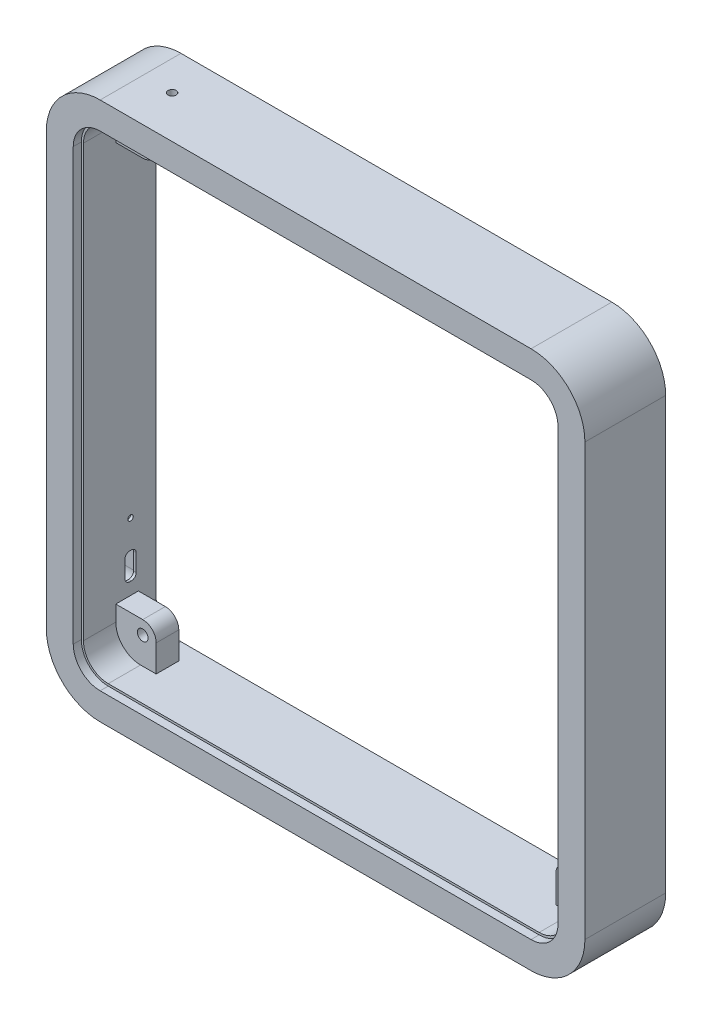
SolidWorks part; units mm, degrees
ref_plane "Piano frontale" through (0, 0, 0) normal (0, 0, 1) x (1, 0, 0)
ref_plane "Piano superiore" through (0, 0, 0) normal (0, 1, 0) x (1, 0, 0)
ref_plane "Piano destro" through (0, 0, 0) normal (1, 0, 0) x (0, 0, -1)
sketch "Sketch2" plane through (0, 0, 0) normal (0, 0, 1) x (1, 0, 0)
  line L5 (-100, -100) -> (100, -100)
  line L6 (-100, -100) -> (-100, 100)
  line L7 (-100, 100) -> (100, 100)
  line L8 (100, -100) -> (100, 100)
  line L9 (-100, -100) -> (100, 100) construction
  line L10 (-100, 100) -> (100, -100) construction
  point P0 (0, 0)
  dimension "D1" = 200
extrude "Boss-Extrude1" add sketch "Sketch2" along normal blind 30
fillet "Fillet1" radius 20 4 edges at (-100, -100, 15) (100, -100, 15) (100, 100, 15) (-100, 100, 15)
sketch "Sketch3" plane through (0, 0, 30) normal (0, 0, 1) x (1, 0, 0)
  line L8 (-90, 80) -> (-90, -80)
  line L9 (-80, -90) -> (80, -90)
  line L10 (90, -80) -> (90, 80)
  line L11 (80, 90) -> (-80, 90)
  line L12 (-90, 80) -> (-90, -80)
  line L13 (-80, -90) -> (80, -90)
  line L14 (90, -80) -> (90, 80)
  line L15 (80, 90) -> (-80, 90)
  arc A8 (-90, -80) -> (-80, -90) centre (-80, -80) ccw
  arc A9 (80, -90) -> (90, -80) centre (80, -80) ccw
  arc A10 (90, 80) -> (80, 90) centre (80, 80) ccw
  arc A11 (-80, 90) -> (-90, 80) centre (-80, 80) ccw
  arc A12 (-90, -80) -> (-80, -90) centre (-80, -80) ccw
  arc A13 (80, -90) -> (90, -80) centre (80, -80) ccw
  arc A14 (90, 80) -> (80, 90) centre (80, 80) ccw
  arc A15 (-80, 90) -> (-90, 80) centre (-80, 80) ccw
  dimension "D1" = 10
extrude "Cut-Extrude1" cut sketch "Sketch3" against normal blind 3
sketch "Sketch4" plane through (0, 0, 27) normal (0, 0, 1) x (1, 0, 0)
  line L16 (-89.2, 80) -> (-89.2, -80)
  line L17 (-80, -89.2) -> (80, -89.2)
  line L18 (89.2, -80) -> (89.2, 80)
  line L19 (80, 89.2) -> (-80, 89.2)
  line L20 (-89.2, 80) -> (-89.2, -80)
  line L21 (-80, -89.2) -> (80, -89.2)
  line L22 (89.2, -80) -> (89.2, 80)
  line L23 (80, 89.2) -> (-80, 89.2)
  arc A16 (-80, 89.2) -> (-89.2, 80) centre (-80, 80) ccw
  arc A17 (-89.2, -80) -> (-80, -89.2) centre (-80, -80) ccw
  arc A18 (80, -89.2) -> (89.2, -80) centre (80, -80) ccw
  arc A19 (89.2, 80) -> (80, 89.2) centre (80, 80) ccw
  arc A20 (-80, 89.2) -> (-89.2, 80) centre (-80, 80) ccw
  arc A21 (-89.2, -80) -> (-80, -89.2) centre (-80, -80) ccw
  arc A22 (80, -89.2) -> (89.2, -80) centre (80, -80) ccw
  arc A23 (89.2, 80) -> (80, 89.2) centre (80, 80) ccw
  dimension "D1" = 0.8
extrude "Cut-Extrude2" cut sketch "Sketch4" against normal through all
sketch "Sketch6" plane through (0, 0, 0) normal (0, 0, -1) x (-1, 0, 0)
  line L1 (-89.2, -74.2) -> (-74.2, -74.2)
  line L2 (-89.2, -74.2) -> (-89.2, -89.2)
  line L3 (-89.2, -89.2) -> (-74.2, -89.2)
  line L4 (-74.2, -74.2) -> (-74.2, -89.2)
  line L5 (-89.2, -80) -> (-89.2, 80) construction
  line L6 (80, -89.2) -> (-80, -89.2) construction
  line L18 (-74.2, 89.2) -> (-74.2, 74.2)
  line L19 (-89.2, 89.2) -> (89.2, 89.2) construction
  line L20 (-89.2, 89.2) -> (-89.2, -89.2) construction
  line L21 (-89.2, -89.2) -> (89.2, -89.2) construction
  line L22 (89.2, 89.2) -> (89.2, -89.2) construction
  line L23 (-89.2, 89.2) -> (89.2, -89.2) construction
  line L24 (-89.2, -89.2) -> (89.2, 89.2) construction
  line L25 (-74.2, 74.2) -> (-89.2, 74.2)
  line L26 (-89.2, 89.2) -> (-89.2, 74.2)
  line L27 (-74.2, 89.2) -> (-89.2, 89.2)
  line L28 (89.2, 74.2) -> (74.2, 74.2)
  line L29 (74.2, 74.2) -> (74.2, 89.2)
  line L30 (89.2, 89.2) -> (74.2, 89.2)
  line L31 (89.2, 74.2) -> (89.2, 89.2)
  line L32 (74.2, -89.2) -> (74.2, -74.2)
  line L33 (74.2, -74.2) -> (89.2, -74.2)
  line L34 (89.2, -89.2) -> (89.2, -74.2)
  line L35 (74.2, -89.2) -> (89.2, -89.2)
  point P14 (0, 0)
  point P19 (0, 0)
  point P24 (0, 0)
  point P29 (0, 0)
  dimension "D2" = 4
  dimension "D1" = 15
extrude "Boss-Extrude4" add sketch "Sketch6" against normal blind 15
fillet "Fillet2" radius 5 4 edges at (74.2, -74.2, 7.5) (-74.2, -74.2, 7.5) (-74.2, 74.2, 7.5) (74.2, 74.2, 7.5)
hole_wizard "Ø4.0 (4) Diameter Hole1" positions "Sketch8" profile "Sketch9" hole size "Ø4.0" standard "ANSI Metric" end condition through all
sketch "Sketch8" plane through (0, 0, 0) normal (0, 0, -1) x (-1, 0, 0)
  point P0 (-79.2, 79.2)
  point P3 (79.2, 79.2)
  point P6 (-79.2, -79.2)
  point P9 (79.2, -79.2)
sketch "Sketch9" plane through (79.2, 79.2, 0) normal (1, 0, 0) x (0, 1, 0)
  line L0 (0, 0) -> (0, 30)
  line L1 (0, 30) -> (2, 30)
  line L2 (2, 30) -> (2, 0)
  line L5 (2, 0) -> (0, 0)
  line L11 (0, -6.35) -> (0, 107.95) construction
  dimension "Thru Hole Dia." = 4
  dimension "Thru Hole Depth" = 30
sketch "Sketch10" plane through (0, 0, 0) normal (0, 0, -1) x (-1, 0, 0)
  line L0 (89.2, -80) -> (89.2, 80)
  line L1 (80, 89.2) -> (-80, 89.2)
  line L2 (-89.2, 80) -> (-89.2, -80)
  line L3 (-80, -89.2) -> (80, -89.2)
  line L4 (90, -80) -> (90, 80)
  line L5 (-80, -90) -> (80, -90)
  line L6 (-90, 80) -> (-90, -80)
  line L7 (80, 90) -> (-80, 90)
  line L8 (90, -80) -> (90, 80) construction
  line L9 (-80, -90) -> (80, -90) construction
  line L10 (-90, 80) -> (-90, -80) construction
  line L11 (80, 90) -> (-80, 90) construction
  arc A0 (89.2, 80) -> (80, 89.2) centre (80, 80) ccw
  arc A1 (-80, 89.2) -> (-89.2, 80) centre (-80, 80) ccw
  arc A2 (-89.2, -80) -> (-80, -89.2) centre (-80, -80) ccw
  arc A3 (80, -89.2) -> (89.2, -80) centre (80, -80) ccw
  arc A4 (90, 80) -> (80, 90) centre (80, 80) ccw
  arc A5 (80, -90) -> (90, -80) centre (80, -80) ccw
  arc A6 (-90, -80) -> (-80, -90) centre (-80, -80) ccw
  arc A7 (-80, 90) -> (-90, 80) centre (-80, 80) ccw
  arc A8 (90, 80) -> (80, 90) centre (80, 80) ccw construction
  arc A9 (80, -90) -> (90, -80) centre (80, -80) ccw construction
  arc A10 (-90, -80) -> (-80, -90) centre (-80, -80) ccw construction
  arc A11 (-80, 90) -> (-90, 80) centre (-80, 80) ccw construction
  dimension "D1" = 0
  dimension "D2" = 0.8
extrude "Cut-Extrude3" cut sketch "Sketch10" against normal blind 6.6
sketch "Sketch11" plane through (0, 100, 0) normal (0, 1, 0) x (1, 0, 0)
  circle A0 centre (-68.955, -14.3249) radius 1.5
extrude "Cut-Extrude4" cut sketch "Sketch11" against normal up to next
sketch "Sketch15" plane through (-89.2, 0, 0) normal (1, 0, 0) x (0, 0, -1)
  line L7 (-9.506, -49.2385) -> (-9.506, -70.1389) construction
  line L9 (-9.226, -59.6887) -> (-9.786, -59.6887)
  line L10 (-7.426, -61.4887) -> (-7.426, -67.8387)
  line L11 (-9.226, -69.6387) -> (-9.786, -69.6387)
  line L36 (-11.586, -61.4887) -> (-11.586, -67.8387)
  line L37 (-7.426, -59.6887) -> (-11.586, -69.6387) construction
  line L38 (-7.426, -69.6387) -> (-11.586, -59.6887) construction
  circle A9 centre (-9.506, -49.2385) radius 1
  arc A10 (-7.426, -67.8387) -> (-9.226, -69.6387) centre (-9.226, -67.8387) cw
  arc A11 (-9.786, -69.6387) -> (-11.586, -67.8387) centre (-9.786, -67.8387) cw
  arc A12 (-9.786, -59.6887) -> (-11.586, -61.4887) centre (-9.786, -61.4887) ccw
  arc A13 (-9.226, -59.6887) -> (-7.426, -61.4887) centre (-9.226, -61.4887) cw
  point P0 (0, 0)
  point P1 (-9.506, -59.6887)
  point P77 (-9.506, -64.6637)
  dimension "D3" = 2
  dimension "D6" = 1.8
  dimension "D4" = 9.95
  dimension "D5" = 4.16
extrude "Cut-Extrude5" cut sketch "Sketch15" against normal through all
sketch "Sketch17" plane through (-100, 0, 0) normal (-1, 0, 0) x (0, 0, 1)
  line L0 (30, -58.1885) -> (0, -58.1885) construction
  line L1 (20.8501, -38.3545) -> (7.5, -38.3545)
  line L2 (2.5, -43.3545) -> (2.5, -72.5)
  line L3 (7.5, -77.5) -> (20.8501, -77.5)
  line L4 (0, 80) -> (0, -80)
  line L5 (0, -80) -> (30, -80)
  line L6 (30, -80) -> (30, 80)
  line L7 (30, 80) -> (0, 80)
  line L8 (0, -58.1885) -> (0, -80) construction
  line L9 (0, -80) -> (30, -80) construction
  line L10 (30, -80) -> (30, -58.1885) construction
  line L12 (25.8501, -72.5) -> (25.8501, -43.3545)
  line L13 (0, 80) -> (0, -80) construction
  arc A0 (7.5, -38.3545) -> (2.5, -43.3545) centre (7.5, -43.3545) ccw
  arc A1 (20.8501, -38.3545) -> (25.8501, -43.3545) centre (20.8501, -43.3545) cw
  arc A2 (2.5, -72.5) -> (7.5, -77.5) centre (7.5, -72.5) ccw
  arc A3 (20.8501, -77.5) -> (25.8501, -72.5) centre (20.8501, -72.5) ccw
  dimension "D5" = 5
  dimension "D4" = 2.5
  dimension "D6" = 2.5
  dimension "D1" = 0
extrude "Cut-Extrude7" cut sketch "Sketch17" against normal offset from surface (9.8 mm away) 1 up to face at (-89.2, -64.6637, 9.506)
fillet "Fillet3" radius 1 16 edges at (-90.2, -77.5, 14.1751) (-90.2, -76.0355, 24.3857) (-90.2, -57.9272, 25.8501) (-90.2, -39.8189, 24.3857) (-90.2, -38.3545, 14.1751) (-90.2, -39.8189, 3.9645) (-90.2, -57.9272, 2.5) (-100, -57.9272, 2.5) (-100, -39.8189, 3.9645) (-100, -38.3545, 14.1751) (-100, -39.8189, 24.3857) (-100, -57.9272, 25.8501) (-100, -76.0355, 24.3857) (-100, -77.5, 14.1751) (-90.2, -76.0355, 3.9645) (-100, -76.0355, 3.9645)
